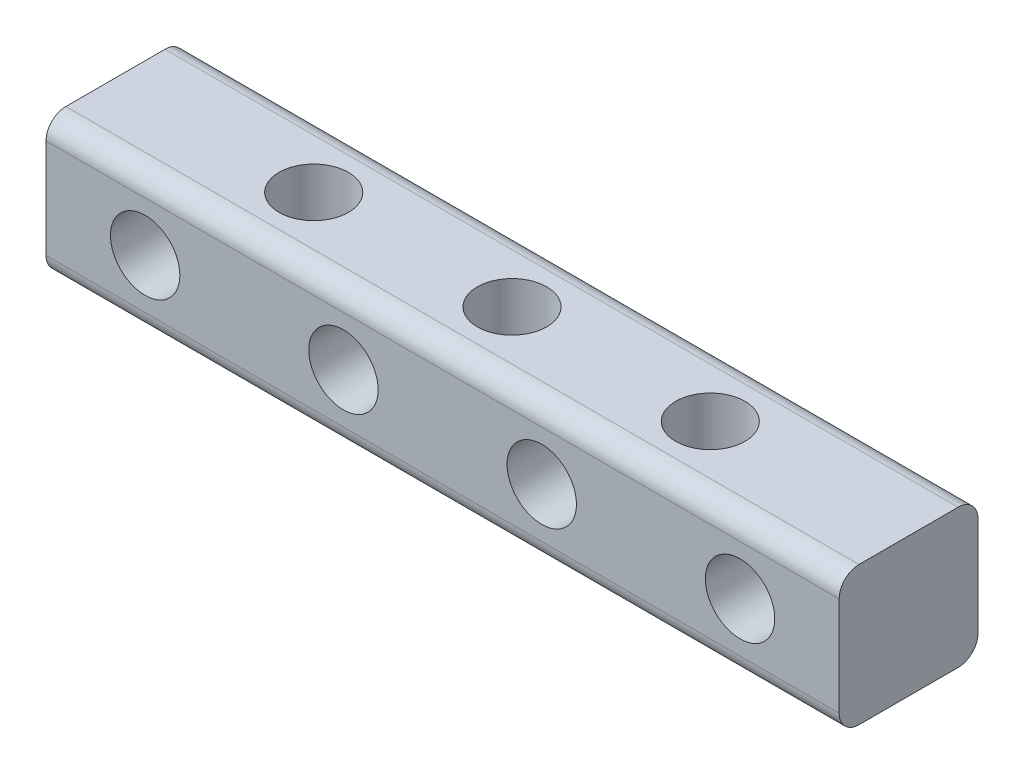
SolidWorks part; units mm, degrees
material "ABS"
ref_plane "前视基准面" through (0, 0, 0) normal (0, 0, 1) x (1, 0, 0)
ref_plane "上视基准面" through (0, 0, 0) normal (0, 1, 0) x (1, 0, 0)
ref_plane "右视基准面" through (0, 0, 0) normal (1, 0, 0) x (0, 0, -1)
sketch "草图1" plane through (0, 0, 0) normal (0, 0, 1) x (1, 0, 0)
  line L0 (0, 3.5) -> (40, 3.5) construction
  line L1 (0, 0) -> (40, 0)
  line L2 (0, 0) -> (0, 7)
  line L3 (0, 7) -> (40, 7)
  line L4 (40, 0) -> (40, 7)
  circle A0 centre (5, 3.5) radius 1.75
  circle A1 centre (15, 3.5) radius 1.75
  circle A2 centre (25, 3.5) radius 1.75
  circle A3 centre (35, 3.5) radius 1.75
  dimension "D2" = 3.5
  dimension "D3" = 3.5
  dimension "D4" = 5
  dimension "D5" = 10
  dimension "D6" = 3.5
  dimension "D7" = 3.5
  dimension "D8" = 10
  dimension "D9" = 10
  dimension "D10" = 5
  dimension "D1" = 7
extrude "凸台-拉伸1" add sketch "草图1" along normal blind 7
sketch "草图2" plane through (0, 7, 0) normal (0, 1, 0) x (1, 0, 0)
  line L0 (0, -3.5) -> (40, -3.5) construction
  line L1 (0, -7) -> (0, 0) construction
  line L2 (40, -7) -> (40, 0) construction
  circle A0 centre (20, -3.5) radius 1.75
  circle A1 centre (30, -3.5) radius 1.75
  circle A2 centre (10, -3.5) radius 1.75
  dimension "D1" = 3.5
  dimension "D2" = 3.5
  dimension "D3" = 10
  dimension "D4" = 10
  dimension "D5" = 3.5
  dimension "D6" = 10
extrude "切除-拉伸1" cut sketch "草图2" against normal blind 7
fillet "圆角1" radius 1 4 edges at (20, 0, 0) (20, 0, 7) (20, 7, 0) (20, 7, 7)
